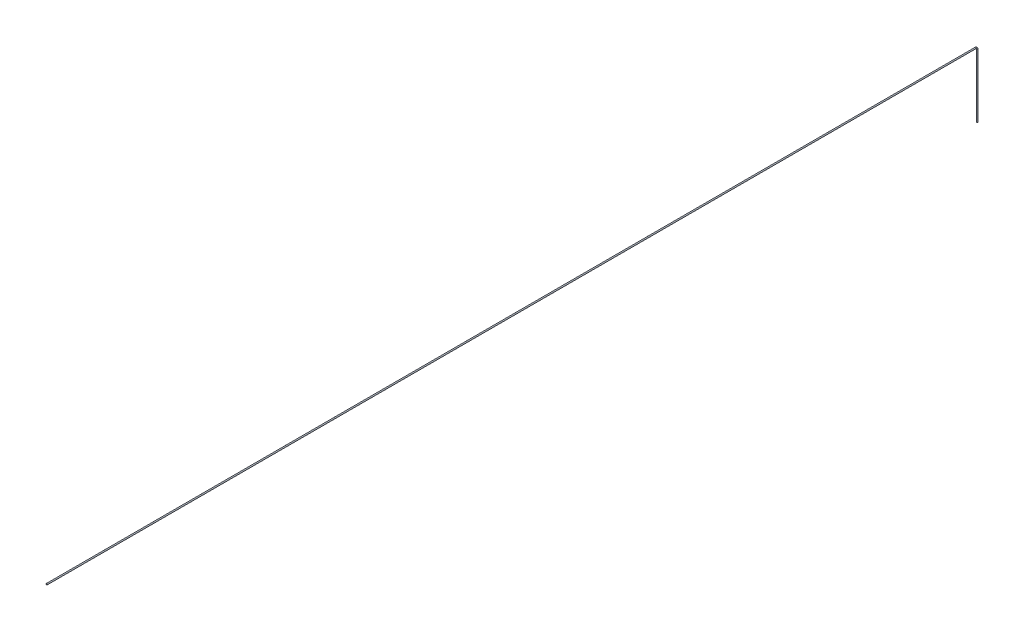
SolidWorks part; units mm, degrees
ref_plane "Front Plane" through (0, 0, 0) normal (0, 0, 1) x (1, 0, 0)
ref_plane "Top Plane" through (0, 0, 0) normal (0, 1, 0) x (1, 0, 0)
ref_plane "Right Plane" through (0, 0, 0) normal (1, 0, 0) x (0, 0, -1)
sketch "Sketch1" plane through (0, 0, 0) normal (1, 0, 0) x (0, 0, -1)
  line L0 (0, 0) -> (0, 5725)
  line L1 (-150, 5875) -> (-84125, 5875)
  arc A0 (0, 5725) -> (-150, 5875) centre (-150, 5725) ccw
  point P6 (0, 5875)
  dimension "D3" = 150
  dimension "D1" = 5875
  dimension "D2" = 84125
sketch "Sketch2" plane through (0, 0, 0) normal (0, 1, 0) x (1, 0, 0)
  circle A0 centre (0, 0) radius 54
  circle A1 centre (0, 0) radius 50
  dimension "D1" = 108
  dimension "D2" = 100
sweep "Sweep1" add profiles "Sketch2" path "Sketch1"
